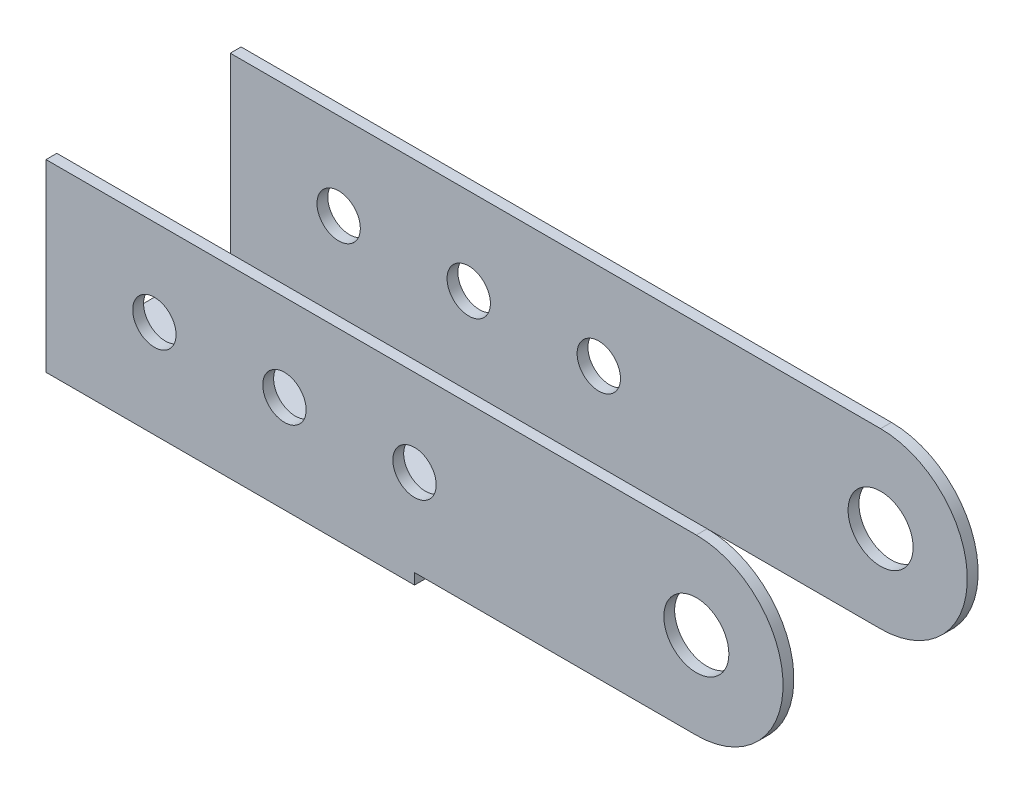
SolidWorks part; units mm, degrees
ref_plane "前视" through (0, 0, 0) normal (0, 0, 1) x (1, 0, 0)
ref_plane "上视" through (0, 0, 0) normal (0, 1, 0) x (1, 0, 0)
ref_plane "右视" through (0, 0, 0) normal (1, 0, 0) x (0, 0, -1)
sketch "草图1" plane through (0, 0, 0) normal (0, 0, 1) x (1, 0, 0)
  line L0 (-10, 12.1517) -> (-10, -12.1517) construction
  line L1 (-15, 4) -> (15, 4)
  line L2 (-15, 4) -> (-15, -4)
  line L3 (-15, -4) -> (15, -4)
  line L4 (-16.7978, 0) -> (28.1127, 0) construction
  line L7 (-4, 14.6585) -> (-4, -12.1517) construction
  line L8 (2, 14.6585) -> (2, -12.1517) construction
  arc A0 (15, -4) -> (15, 4) centre (15, 0) ccw
  circle A1 centre (15, 0) radius 1.5
  circle A2 centre (-10, 0) radius 1
  circle A3 centre (-4, 0) radius 1
  circle A4 centre (2, 0) radius 1
  point P0 (0, 0)
  dimension "D3" = 8
  dimension "D4" = 3
  dimension "D8" = 2
  dimension "D9" = 2
  dimension "D10" = 2
  dimension "D1" = 8
  dimension "D2" = 30
  dimension "D5" = 5
  dimension "D6" = 11
  dimension "D7" = 17
ref_plane "基准面1" through (0, 0, 8) normal (0, 0, 1) x (1, 0, 0)
sketch "草图2" plane through (0, 0, 8) normal (0, 0, 1) x (1, 0, 0)
  line L3 (15, 4) -> (-15, 4)
  line L4 (-15, -4) -> (15, -4)
  line L5 (-15, 4) -> (-15, -4)
  line L6 (15, 4) -> (-15, 4)
  line L7 (-15, -4) -> (15, -4)
  line L8 (-15, 4) -> (-15, -4)
  circle A1 centre (15, 0) radius 1.5
  circle A2 centre (15, 0) radius 1.5
  arc A3 (15, -4) -> (15, 4) centre (15, 0) ccw
  arc A4 (15, -4) -> (15, 4) centre (15, 0) ccw
  circle A5 centre (2, 0) radius 1
  circle A6 centre (2, 0) radius 1
  circle A7 centre (-4, 0) radius 1
  circle A8 centre (-4, 0) radius 1
  circle A9 centre (-10, 0) radius 1
  circle A10 centre (-10, 0) radius 1
  dimension "D1" = 0
  dimension "D2" = 0
  dimension "D3" = 0
  dimension "D4" = 0
  dimension "D5" = 0
extrude "凸台-拉伸1" add sketch "草图2" along normal blind 0.5
extrude "凸台-拉伸2" add sketch "草图1" against normal blind 0.5 separate body
ref_plane "基准面2" through (0, -4, 0) normal (0, -1, 0) x (-1, 0, 0)
sketch "草图3" plane through (0, -4, 0) normal (0, -1, 0) x (-1, 0, 0)
  line L0 (-2, 0.5) -> (15, 0.5)
  line L1 (-2, 0.5) -> (-2, 0) construction
  line L2 (15, 0.5) -> (-15, 0.5) construction
  line L3 (15, 0.5) -> (15, -8.5)
  line L4 (15, -8.5) -> (-2, -8.5)
  line L5 (-2, -8.5) -> (-2, -8) construction
  line L6 (15, -8.5) -> (-15, -8.5) construction
  line L7 (-2, -8.5) -> (-2, 0.5)
extrude "凸台-拉伸3" add sketch "草图3" along normal blind 0.5
